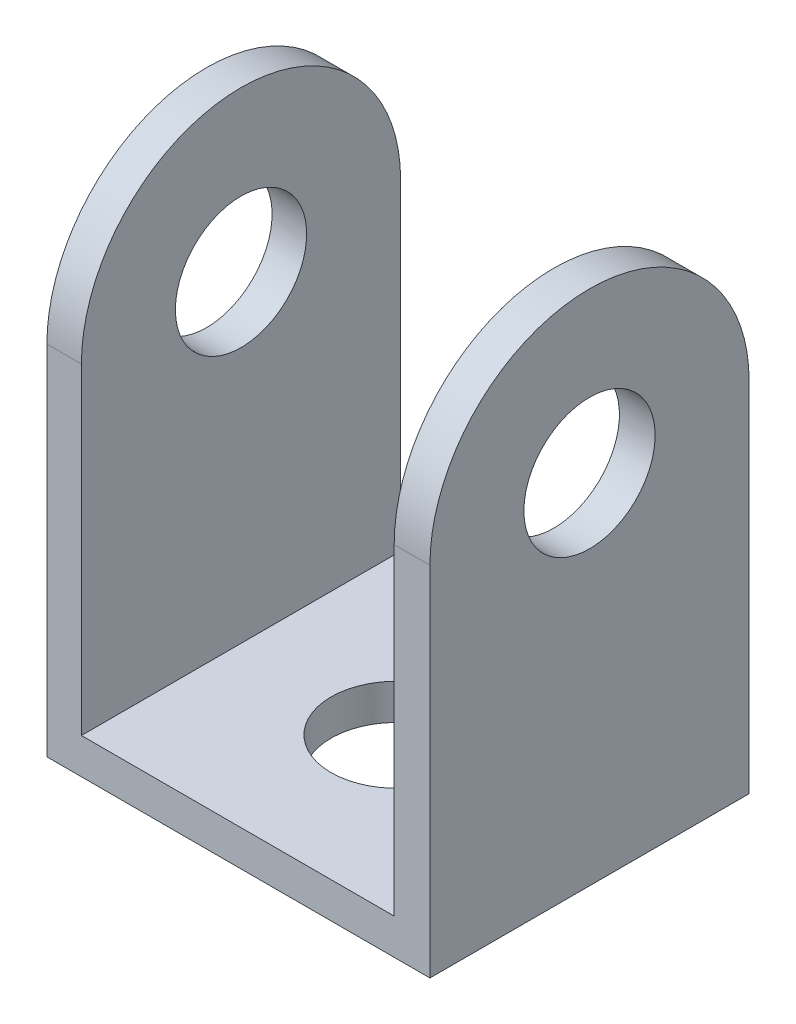
SolidWorks part; units mm, degrees
material "6061-T6 (SS)"
ref_plane "Front Plane" through (0, 0, 0) normal (0, 0, 1) x (1, 0, 0)
ref_plane "Top Plane" through (0, 0, 0) normal (0, 1, 0) x (1, 0, 0)
ref_plane "Right Plane" through (0, 0, 0) normal (1, 0, 0) x (0, 0, -1)
sketch "Sketch2" plane through (0, 0, 0) normal (1, 0, 0) x (0, 0, -1)
  line L0 (-7.9375, 0) -> (-7.9375, -17.78)
  line L1 (-7.9375, -17.78) -> (7.9375, -17.78)
  line L2 (7.9375, -17.78) -> (7.9375, 0)
  circle A0 centre (0, 0) radius 3.2639
  circle A1 centre (0, 0) radius 7.9375
  dimension "D1" = 6.5278
  dimension "D2" = 15.875
  dimension "D3" = 17.78
extrude "Boss-Extrude1" add sketch "Sketch2" along normal blind 19.05 contours A1 L0 L1 L2 | A1 A0
sketch "Sketch3" plane through (0, 0, 0) normal (0, 0, 1) x (1, 0, 0)
  line L0 (19.05, 0) -> (19.05, -17.78) construction
  line L1 (1.717, -16.002) -> (17.272, -16.002)
  line L2 (1.717, -16.002) -> (1.717, 9.398)
  line L3 (1.717, 9.398) -> (17.272, 9.398)
  line L4 (17.272, -16.002) -> (17.272, 9.398)
  line L5 (1.717, -16.002) -> (17.272, 9.398) construction
  line L6 (1.717, 9.398) -> (17.272, -16.002) construction
  line L7 (0, 0) -> (0, -17.78) construction
  line L8 (19.05, -17.78) -> (0, -17.78) construction
  point P0 (9.4945, -3.302)
  dimension "D1" = 1.778
  dimension "D2" = 1.717
  dimension "D3" = 1.778
  dimension "D4" = 25.4
extrude "Cut-Extrude1" cut sketch "Sketch3" against normal mid plane 25.4
sketch "Sketch4" plane through (0, 0, 0) normal (0, 1, 0) x (1, 0, 0)
  line L0 (1.717, 7.9375) -> (17.272, 7.9375) construction
  circle A0 centre (9.525, -0.0635) radius 3.2639
  dimension "D3" = 6.5278
  dimension "D1" = 9.525
  dimension "D2" = 8.001
extrude "Cut-Extrude2" cut sketch "Sketch4" against normal through all
sketch3d "3DSketch1"
  line L0 (0, 0, 0) -> (19.05, 0, 0) construction
  line L1 (19.05, 0, 0) -> (17.272, 0, 0) construction
  line L2 (9.525, 0, 0) -> (9.525, 0, 7.1009) construction
  line L3 (9.525, 0, 0) -> (9.525, -7.9855, 0) construction
  line L4 (0.7251, 0, 0) -> (-8.7999, 0, 0) construction
